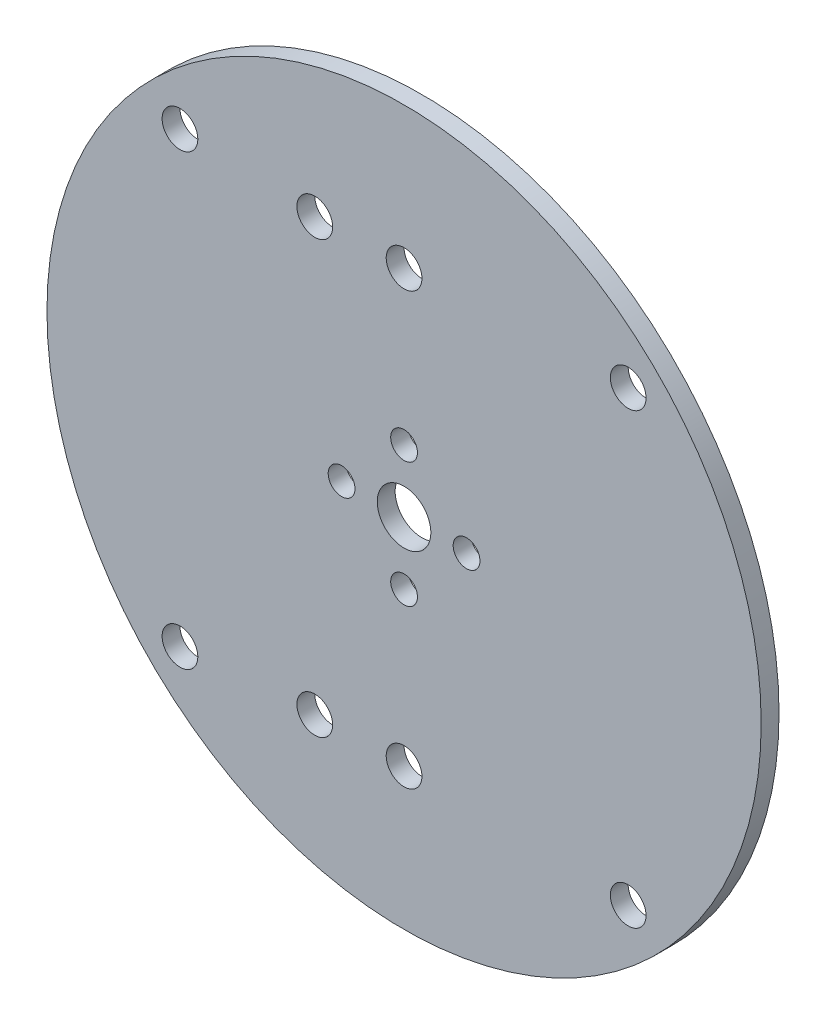
SolidWorks part; units mm, degrees
material "普通碳钢"
ref_plane "前视" through (0, 0, 0) normal (0, 0, 1) x (1, 0, 0)
ref_plane "上视" through (0, 0, 0) normal (0, 1, 0) x (1, 0, 0)
ref_plane "右视" through (0, 0, 0) normal (1, 0, 0) x (0, 0, -1)
sketch "草图1" plane through (0, 0, 0) normal (0, 0, 1) x (1, 0, 0)
  circle A0 centre (89.8449, 65.6716) radius 2
  circle A1 centre (39.6403, 15.467) radius 2
  circle A2 centre (39.6403, 65.6716) radius 2
  circle A3 centre (54.7426, 64.7143) radius 2
  circle A4 centre (64.7426, 64.7143) radius 2
  circle A5 centre (89.8449, 15.467) radius 2
  circle A6 centre (64.7426, 16.4143) radius 2
  circle A7 centre (57.7426, 40.5693) radius 1.5
  circle A8 centre (64.7426, 33.5693) radius 1.5
  circle A9 centre (71.7426, 40.5693) radius 1.5
  circle A10 centre (64.7426, 47.5693) radius 1.5
  circle A11 centre (64.7426, 40.5693) radius 3
  circle A12 centre (64.7426, 40.5693) radius 40
  circle A13 centre (54.7426, 16.4143) radius 2
  dimension "D1" = 4
  dimension "D2" = 80
  dimension "D3" = 25.1023
extrude "凸台-拉伸1" add sketch "草图1" along normal blind 2
